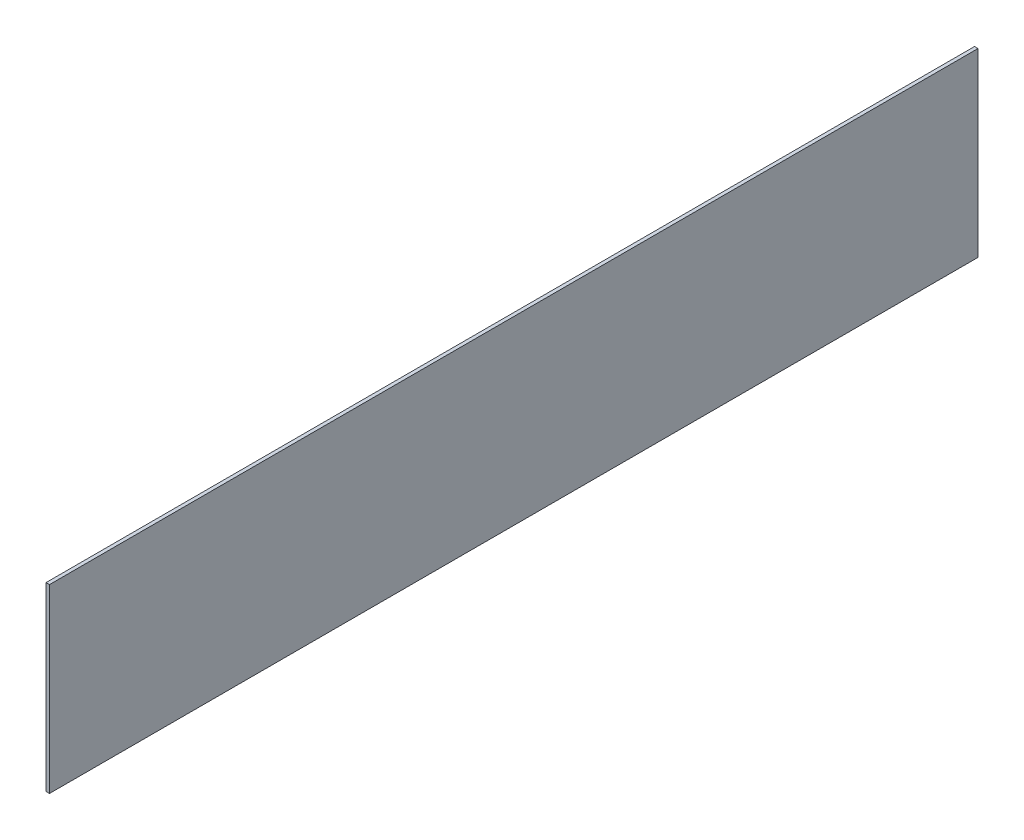
SolidWorks part; units mm, degrees
ref_plane "Front Plane" through (0, 0, 0) normal (0, 0, 1) x (1, 0, 0)
ref_plane "Top Plane" through (0, 0, 0) normal (0, 1, 0) x (1, 0, 0)
ref_plane "Right Plane" through (0, 0, 0) normal (1, 0, 0) x (0, 0, -1)
sketch "Sketch1" plane through (0, 0, 0) normal (1, 0, 0) x (0, 0, -1)
  line L1 (-4007.984, 780.9711) -> (3998.016, 780.9711)
  line L2 (-4007.984, 780.9711) -> (-4007.984, -779.0289)
  line L4 (3998.016, 780.9711) -> (3998.016, -779.0289)
  line L5 (-4007.984, 780.9711) -> (3998.016, -779.0289) construction
  line L6 (-1400.5895, -273.5907) -> (3998.016, 780.9711) construction
  line L15 (-4007.984, -779.0289) -> (3998.016, -779.0289)
  point P0 (0, 0)
  dimension "D1" = 1560
  dimension "D2" = 8006
  dimension "D6" = 1560
extrude "Boss-Extrude1" add sketch "Sketch1" along normal blind 30
